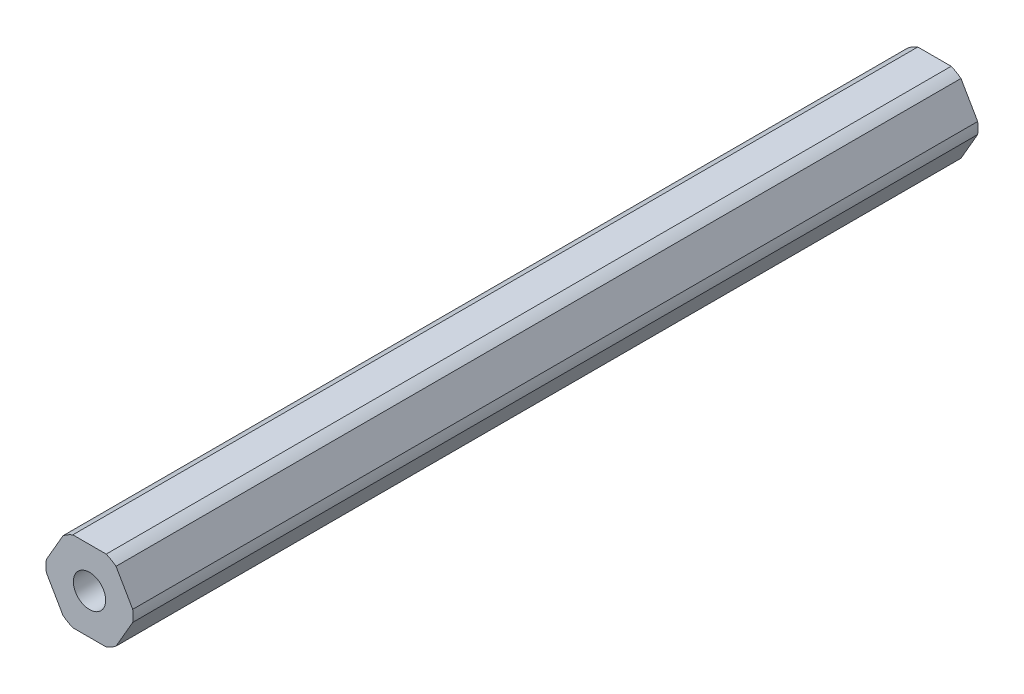
SolidWorks part; units mm, degrees
ref_plane "Front Plane" through (0, 0, 0) normal (0, 0, 1) x (1, 0, 0)
ref_plane "Top Plane" through (0, 0, 0) normal (0, 1, 0) x (1, 0, 0)
ref_plane "Right Plane" through (0, 0, 0) normal (1, 0, 0) x (0, 0, -1)
sketch "Sketch1" plane through (0, 0, 0) normal (0, 0, 1) x (1, 0, 0)
  line L1 (2.635, 6.35) -> (-2.635, 6.35)
  line L2 (-4.1818, 5.457) -> (-6.8168, 0.893)
  line L3 (-6.8168, -0.893) -> (-4.1818, -5.457)
  line L4 (-2.635, -6.35) -> (2.635, -6.35)
  line L5 (4.1818, -5.457) -> (6.8168, -0.893)
  line L6 (6.8168, 0.893) -> (4.1818, 5.457)
  circle A0 centre (0, 0) radius 6.35 construction
  arc A1 (-2.635, 6.35) -> (-4.1818, 5.457) centre (0, 0) ccw
  arc A2 (4.1818, 5.457) -> (2.635, 6.35) centre (0, 0) ccw
  arc A3 (6.8168, -0.893) -> (6.8168, 0.893) centre (0, 0) ccw
  arc A4 (2.635, -6.35) -> (4.1818, -5.457) centre (0, 0) ccw
  arc A5 (-4.1818, -5.457) -> (-2.635, -6.35) centre (0, 0) ccw
  arc A6 (-6.8168, 0.893) -> (-6.8168, -0.893) centre (0, 0) ccw
  circle A7 centre (0, 0) radius 2.55
  dimension "D1" = 12.7
  dimension "D2" = 13.75
  dimension "D3" = 5.1
extrude "Boss-Extrude1" add sketch "Sketch1" along normal blind 133.35
